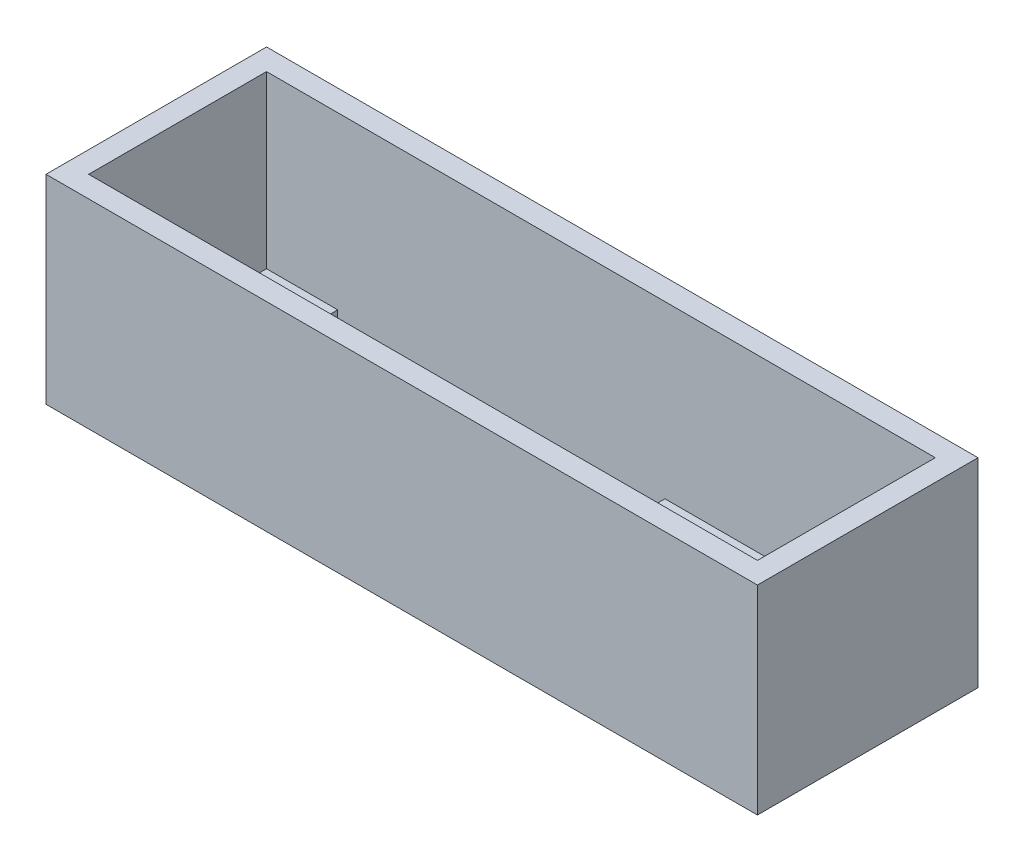
SolidWorks part; units mm, degrees
ref_plane "前视基准面" through (0, 0, 0) normal (0, 0, 1) x (1, 0, 0)
ref_plane "上视基准面" through (0, 0, 0) normal (0, 1, 0) x (1, 0, 0)
ref_plane "右视基准面" through (0, 0, 0) normal (1, 0, 0) x (0, 0, -1)
sketch "草图1" plane through (0, 0, 0) normal (0, 1, 0) x (1, 0, 0)
  line L1 (0, 0) -> (50, 0)
  line L2 (0, 0) -> (0, 15.5)
  line L3 (0, 15.5) -> (50, 15.5)
  line L4 (50, 0) -> (50, 15.5)
  dimension "D1" = 15.5
  dimension "D2" = 50
extrude "凸台-拉伸1" add sketch "草图1" along normal blind 14
sketch "草图2" plane through (0, 14, 0) normal (0, 1, 0) x (1, 0, 0)
  line L8 (1.5, 14) -> (1.5, 1.5)
  line L9 (1.5, 1.5) -> (48.5, 1.5)
  line L10 (48.5, 1.5) -> (48.5, 14)
  line L11 (48.5, 14) -> (1.5, 14)
  line L12 (1.5, 14) -> (1.5, 1.5)
  line L13 (1.5, 1.5) -> (48.5, 1.5)
  line L14 (48.5, 1.5) -> (48.5, 14)
  line L15 (48.5, 14) -> (1.5, 14)
  dimension "D1" = 1.5
extrude "切除-拉伸1" cut sketch "草图2" against normal offset from surface (12 mm away) 2 up to face at (25, 0, -7.75)
sketch "草图4" plane through (0, 2, 0) normal (0, 1, 0) x (1, 0, 0)
  line L0 (48.5, 14) -> (1.5, 14) construction
  line L1 (6.5, 14) -> (29.5, 14)
  line L2 (6.5, 14) -> (6.5, 1.5)
  line L3 (6.5, 1.5) -> (29.5, 1.5)
  line L4 (29.5, 14) -> (29.5, 1.5)
  line L5 (1.5, 1.5) -> (48.5, 1.5) construction
  line L6 (48.5, 14) -> (1.5, 14) construction
  line L7 (1.5, 7.75) -> (60.2228, 7.75) construction
  line L8 (1.5, 14) -> (1.5, 1.5) construction
  line L9 (1.5, 14) -> (1.5, 1.5) construction
  line L10 (18, 14) -> (18, -8.8667) construction
  circle A0 centre (4.1, 7.75) radius 1.15
  circle A1 centre (31.9, 7.75) radius 1.15
  circle A2 centre (12.85, 7.75) radius 1.8755 construction
  circle A3 centre (39.65, 7.75) radius 1.8069
  point P24 (3.8867, 7.75)
  point P25 (18, 14)
  point P26 (18, 14)
  point P29 (18, 14)
  dimension "D3" = 2.3
  dimension "D5" = 27.8
  dimension "D7" = 8.75
  dimension "D8" = 26.8
  dimension "D1" = 5
  dimension "D2" = 23
extrude "切除-拉伸2" cut sketch "草图4" against normal blind 2
